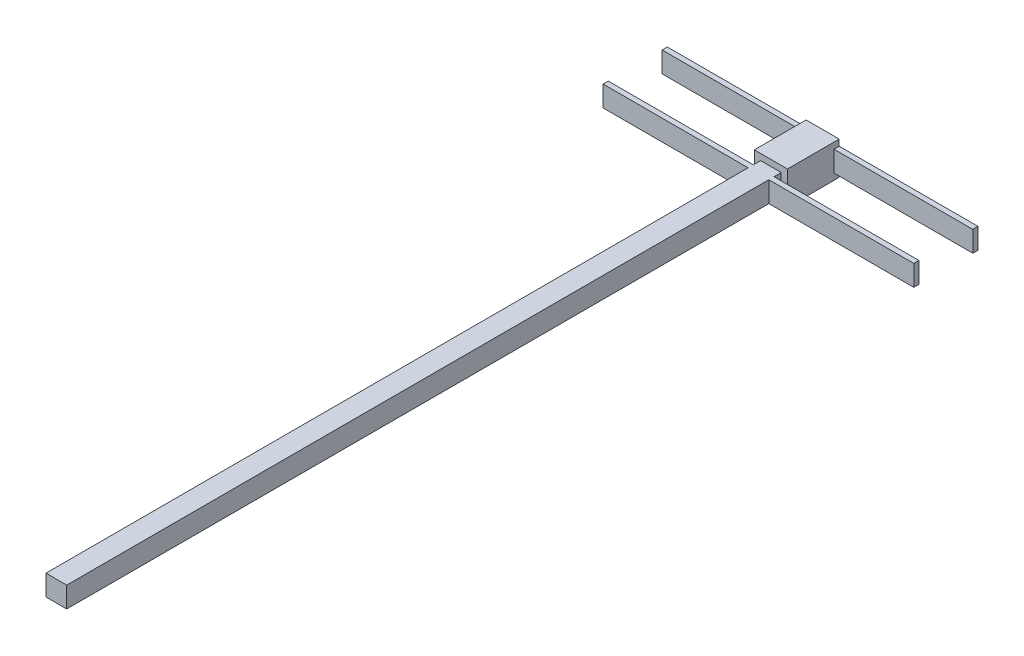
SolidWorks part; units mm, degrees
ref_plane "前视基准面" through (0, 0, 0) normal (0, 0, 1) x (1, 0, 0)
ref_plane "上视基准面" through (0, 0, 0) normal (0, 1, 0) x (1, 0, 0)
ref_plane "右视基准面" through (0, 0, 0) normal (1, 0, 0) x (0, 0, -1)
other "Configuration Table"
sketch "草图1" plane through (0, 0, 0) normal (0, 0, 1) x (1, 0, 0)
  line L1 (-10, 10) -> (10, 10)
  line L2 (-10, 10) -> (-10, -10)
  line L3 (-10, -10) -> (10, -10)
  line L4 (10, 10) -> (10, -10)
  line L5 (-10, 10) -> (10, -10) construction
  line L6 (-10, -10) -> (10, 10) construction
  point P0 (0, 0)
extrude "凸台-拉伸1" add sketch "草图1" along normal blind 690
sketch "草图2" plane through (0, 0, 0) normal (0, 0, -1) x (-1, 0, 0)
  line L1 (-16, 16) -> (16, 16)
  line L2 (-16, 16) -> (-16, -16)
  line L3 (-16, -16) -> (16, -16)
  line L4 (16, 16) -> (16, -16)
  line L5 (-16, 16) -> (16, -16) construction
  line L6 (-16, -16) -> (16, 16) construction
  point P0 (0, 0)
extrude "凸台-拉伸2" add sketch "草图2" along normal blind 50
sketch "草图3" plane through (0, 0, -50) normal (0, 0, -1) x (-1, 0, 0)
  line L1 (-15, 15) -> (15, 15)
  line L2 (-15, 15) -> (-15, -15)
  line L3 (-15, -15) -> (15, -15)
  line L4 (15, 15) -> (15, -15)
  line L5 (-15, 15) -> (15, -15) construction
  line L6 (-15, -15) -> (15, 15) construction
  point P0 (0, 0)
extrude "切除-拉伸1" cut sketch "草图3" against normal blind 46
sketch "草图4" plane through (0, 10, 0) normal (0, 1, 0) x (1, 0, 0)
  line L0 (-16, 50) -> (16, 50) construction
  line L1 (-150, 45) -> (150, 45)
  line L2 (-150, 45) -> (-150, 50)
  line L3 (-150, 50) -> (150, 50)
  line L4 (150, 45) -> (150, 50)
extrude "凸台-拉伸3" add sketch "草图4" against normal blind 20
pattern_linear "阵列(线性)1" count 2 spacing 57 along (0, 0, 1) of "凸台-拉伸3"
